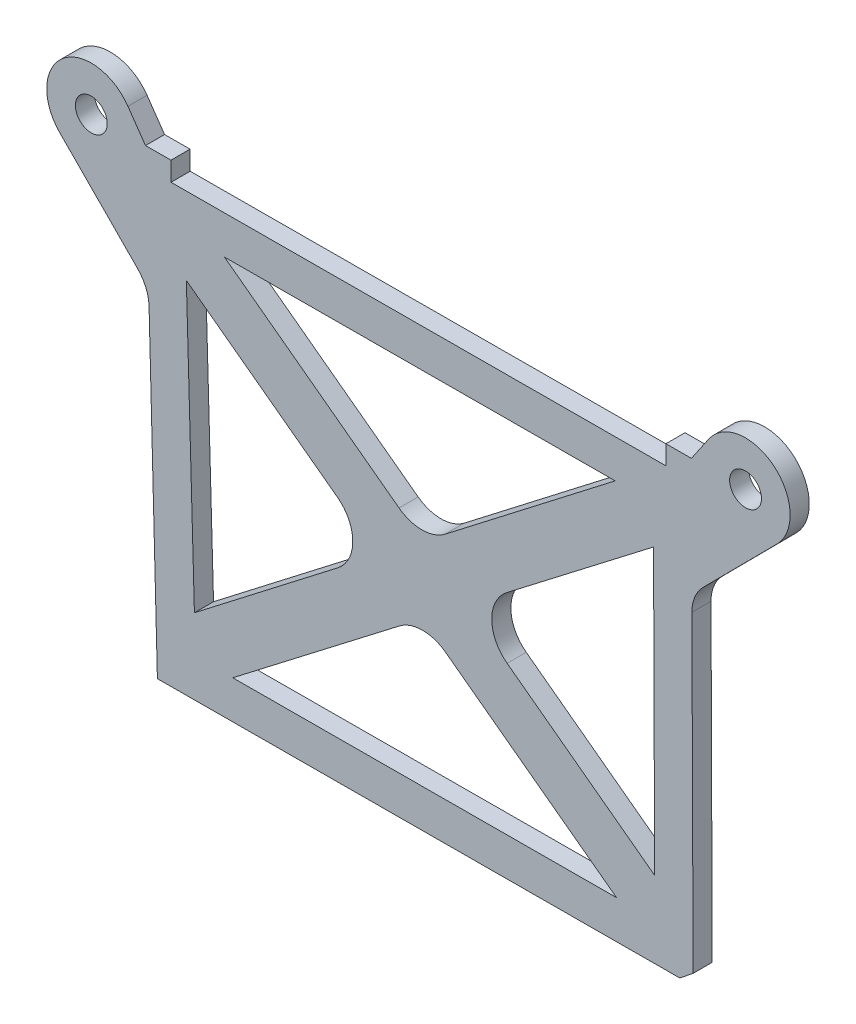
SolidWorks part; units mm, degrees
ref_plane "前视基准面" through (0, 0, 0) normal (0, 0, 1) x (1, 0, 0)
ref_plane "上视基准面" through (0, 0, 0) normal (0, 1, 0) x (1, 0, 0)
ref_plane "右视基准面" through (0, 0, 0) normal (1, 0, 0) x (0, 0, -1)
sketch "草图1" plane through (0, 0, 0) normal (0, 0, 1) x (1, 0, 0)
  line L0 (35.4275, 24.0131) -> (48.7686, 34.3051)
  line L1 (48.7686, 34.3051) -> (18.0995, 34.1873)
  line L2 (18.0995, 34.1873) -> (31.8033, 23.9823)
  line L3 (40.2877, 17.664) -> (51.8656, 9.0421)
  line L4 (51.8656, 9.0421) -> (51.7801, 31.3166)
  line L5 (51.7801, 31.3166) -> (40.2504, 22.4481)
  line L6 (26.9641, 22.3018) -> (15.1122, 31.1021)
  line L7 (15.1122, 31.1021) -> (15.7451, 8.8291)
  line L8 (15.7451, 8.8291) -> (27.008, 17.5179)
  line L9 (48.8772, 6.0306) -> (35.448, 16.0022)
  line L10 (31.8305, 15.9715) -> (18.7555, 5.9143)
  line L11 (18.7555, 5.9143) -> (48.8772, 6.0306)
  line L12 (61.4856, 36.379) -> (55.6619, 30.5104)
  line L13 (54.7914, 28.3858) -> (54.8854, 3.886)
  line L14 (54.8854, 3.886) -> (53.8395, 3.0497)
  line L15 (53.8395, 3.0497) -> (12.8398, 2.8922)
  line L16 (12.8398, 2.8922) -> (12.1843, 27.9428)
  line L17 (11.2847, 29.9938) -> (6.39, 34.9471)
  line L18 (6.39, 34.9471) -> (5.1885, 36.1629)
  line L19 (10.5286, 40.6437) -> (11.9038, 38.6636)
  line L20 (11.9038, 38.6636) -> (13.9038, 38.6712)
  line L21 (13.9038, 38.6712) -> (13.9096, 37.1712)
  line L22 (13.9096, 37.1712) -> (52.7571, 37.3204)
  line L23 (52.7571, 37.3204) -> (52.7513, 38.8204)
  line L24 (52.7513, 38.8204) -> (54.7513, 38.8281)
  line L25 (54.7513, 38.8281) -> (56.1113, 40.8188)
  arc A0 (31.8033, 23.9823) -> (35.4275, 24.0131) centre (33.5951, 26.3884) ccw
  arc A1 (40.2504, 22.4481) -> (40.2877, 17.664) centre (42.0795, 20.0701) ccw
  arc A2 (27.008, 17.5179) -> (26.9641, 22.3018) centre (25.1756, 19.8932) ccw
  arc A3 (35.448, 16.0022) -> (31.8305, 15.9715) centre (33.6596, 13.5936) ccw
  circle A4 centre (59.0012, 38.8444) radius 1.25
  circle A5 centre (7.6539, 38.6472) radius 1.25
  arc A6 (55.6619, 30.5104) -> (54.7914, 28.3858) centre (57.7914, 28.3973) ccw
  arc A7 (12.1843, 27.9428) -> (11.2847, 29.9938) centre (9.0884, 27.8076) ccw
  arc A8 (10.5286, 40.6437) -> (5.1885, 36.1629) centre (7.6539, 38.6472) ccw
  arc A9 (61.4856, 36.379) -> (56.1113, 40.8188) centre (59.0012, 38.8444) ccw
extrude "凸台-拉伸1" add sketch "草图1" along normal blind 1.5
